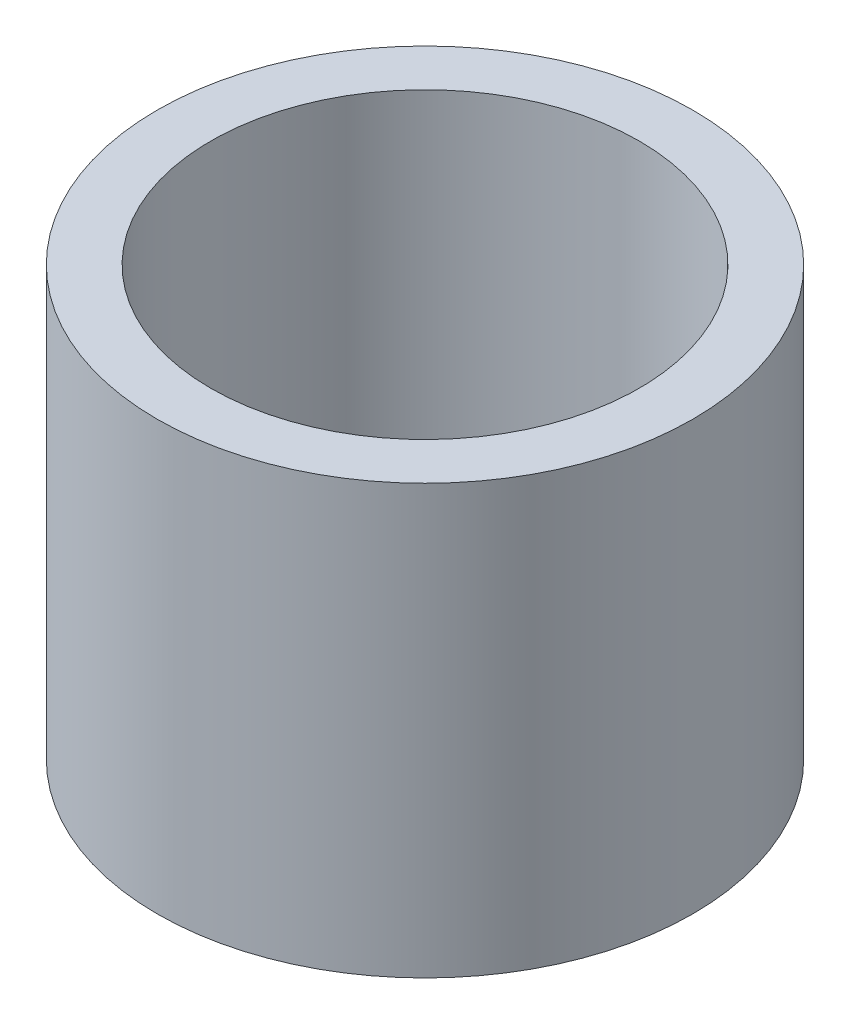
SolidWorks part; units mm, degrees
ref_plane "Front Plane" through (0, 0, 0) normal (0, 0, 1) x (1, 0, 0)
ref_plane "Top Plane" through (0, 0, 0) normal (0, 1, 0) x (1, 0, 0)
ref_plane "Right Plane" through (0, 0, 0) normal (1, 0, 0) x (0, 0, -1)
sketch "Sketch1" plane through (0, 0, 0) normal (0, 1, 0) x (1, 0, 0)
  circle A0 centre (0, 0) radius 25.4
  circle A1 centre (0, 0) radius 31.75
  dimension "D1" = 6.35
  dimension "D2" = 50.8
extrude "Boss-Extrude1" add sketch "Sketch1" along normal blind 50.8
